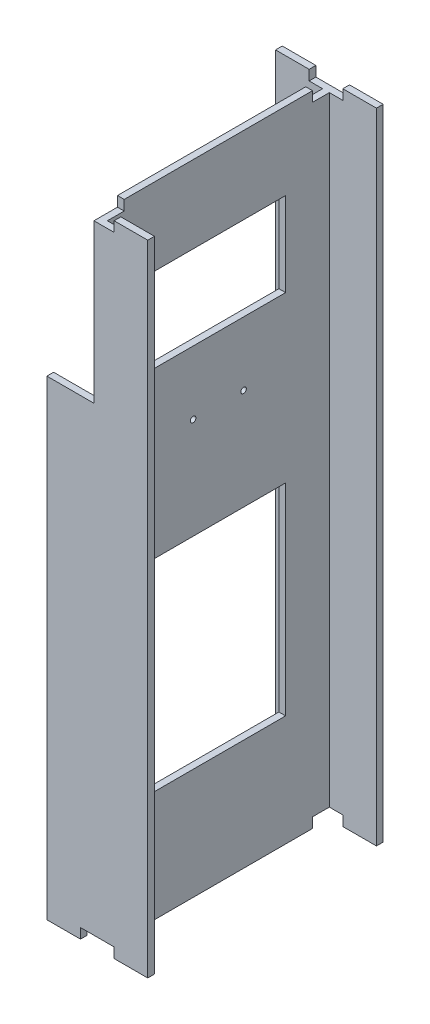
SolidWorks part; units mm, degrees
ref_plane "Front Plane" through (0, 0, 0) normal (0, 0, 1) x (1, 0, 0)
ref_plane "Top Plane" through (0, 0, 0) normal (0, 1, 0) x (1, 0, 0)
ref_plane "Right Plane" through (0, 0, 0) normal (1, 0, 0) x (0, 0, -1)
sketch "Sketch1" plane through (0, 0, 0) normal (0, 1, 0) x (1, 0, 0)
  line L0 (0, 0) -> (0, 66)
  line L2 (-16, 66) -> (-16, 68)
  line L3 (-16, 68) -> (14, 68)
  line L4 (14, 68) -> (14, 66)
  line L6 (-2, 66) -> (-2, 0)
  line L8 (14, 0) -> (14, -2)
  line L9 (14, -2) -> (-16, -2)
  line L10 (-16, -2) -> (-16, 0)
  line L12 (-16, 66) -> (-2, 66)
  line L13 (0, 66) -> (14, 66)
  line L14 (0, 0) -> (14, 0)
  line L15 (-2, 0) -> (-16, 0)
  dimension "D1" = 30
  dimension "D3" = 2
  dimension "D4" = 70
extrude "Boss-Extrude1" add sketch "Sketch1" along normal blind 95
sketch "Sketch3" plane through (0, 0, 0) normal (0, -1, 0) x (1, 0, 0)
  line L0 (48.883, 0) -> (-50.883, 0) construction
  line L1 (48.883, -66) -> (-50.883, -66) construction
  line L2 (-6, 5) -> (4, 5)
  line L3 (-6, 5) -> (-6, -5)
  line L4 (-6, -5) -> (4, -5)
  line L5 (4, 5) -> (4, -5)
  line L6 (-6, 5) -> (4, -5) construction
  line L7 (-6, -5) -> (4, 5) construction
  line L8 (-6, -61) -> (4, -61)
  line L9 (-6, -61) -> (-6, -71)
  line L10 (-6, -71) -> (4, -71)
  line L11 (4, -61) -> (4, -71)
  line L12 (-6, -61) -> (4, -71) construction
  line L13 (-6, -71) -> (4, -61) construction
  line L14 (-2, 0) -> (0, 0) construction
  line L15 (-2, -66) -> (0, -66) construction
  point P3 (-1, 0)
  point P9 (-1, -66)
  point P19 (-1, 0)
  point P24 (-1, -66)
  dimension "D1" = 10
  dimension "D2" = 10
extrude "Cut-Extrude2" cut sketch "Sketch3" against normal blind 3
mirror "Mirror2" about plane through (0, 95, 0) normal (0, -1, 0) of bodies 103
sketch "Sketch4" plane through (-2, 0, 0) normal (-1, 0, 0) x (0, 0, 1)
  line L0 (-53, 100) -> (-66, 100) construction
  line L1 (-13, 100) -> (0, 100) construction
  line L6 (-53, 167) -> (-53, 142)
  line L7 (-53, 142) -> (-13, 142)
  line L8 (-53, 167) -> (-13, 167)
  line L9 (-53, 167) -> (-53, 33) construction
  line L10 (-53, 33) -> (-13, 33)
  line L11 (-13, 167) -> (-13, 33) construction
  line L12 (-13, 142) -> (-13, 167)
  line L13 (-53, 33) -> (-53, 93)
  line L14 (-53, 93) -> (-13, 93)
  line L15 (-13, 93) -> (-13, 33)
  line L23 (-61, 0) -> (-5, 0)
  line L24 (-5, 0) -> (-5, 3)
  line L25 (-5, 3) -> (0, 3)
  line L26 (0, 3) -> (0, 187)
  line L27 (0, 187) -> (-5, 187)
  line L28 (-5, 187) -> (-5, 190)
  line L29 (-5, 190) -> (-61, 190)
  line L30 (-61, 190) -> (-61, 187)
  line L31 (-61, 187) -> (-66, 187)
  line L32 (-66, 187) -> (-66, 3)
  line L33 (-66, 3) -> (-61, 3)
  line L34 (-61, 3) -> (-61, 0)
  line L35 (-61, 0) -> (-5, 0) construction
  line L36 (-5, 0) -> (-5, 3) construction
  line L37 (-5, 3) -> (0, 3) construction
  line L38 (0, 3) -> (0, 187) construction
  line L39 (0, 187) -> (-5, 187) construction
  line L40 (-5, 187) -> (-5, 190) construction
  line L41 (-5, 190) -> (-61, 190) construction
  line L42 (-61, 190) -> (-61, 187) construction
  line L43 (-61, 187) -> (-66, 187) construction
  line L44 (-66, 187) -> (-66, 3) construction
  line L45 (-66, 3) -> (-61, 3) construction
  line L46 (-61, 3) -> (-61, 0) construction
  dimension "D1" = 30
  dimension "D3" = 40
  dimension "D2" = 20
  dimension "D5" = 60
  dimension "D6" = 25
  dimension "D4" = 0
extrude "Cut-Extrude8" cut sketch "Sketch4" against normal blind 2
sketch "Sketch5" plane through (0, 0, 0) normal (0, 0, -1) x (-1, 0, 0)
  line L1 (2, 190) -> (16, 190)
  line L2 (2, 190) -> (2, 140)
  line L3 (2, 140) -> (16, 140)
  line L4 (16, 190) -> (16, 140)
  line L5 (2, 187) -> (2, 3) construction
  point P5 (9.518, 195.2569)
  point P6 (-6.1067, 194.6282)
  point P7 (0, 169.7844)
  point P8 (0, 0)
  point P10 (3.0538, 160)
  dimension "D1" = 50
extrude "Cut-Extrude9" cut sketch "Sketch5" against normal up to surface (2 mm away) up to face at (-1, 95, 2)
sketch "Sketch6" plane through (0, 0, 0) normal (1, 0, 0) x (0, 0, -1)
  circle A0 centre (40.5, 123.0748) radius 0.825 construction
  circle A1 centre (25.5, 123.0748) radius 0.825 construction
  circle A2 centre (40.5, 123.0748) radius 0.825
  circle A3 centre (25.5, 123.0748) radius 0.825
extrude "Cut-Extrude10" cut sketch "Sketch6" against normal through all
equation "\"w_BeamWidth\"=30"
equation "\"D1@Sketch1\"=\"w_BeamWidth\""
equation "\"TBeam\"=2"
equation "\"D2@Sketch1\"=\"TBeam\""
equation "\"D3@Sketch1\"=\"TBeam\""
equation "\"BeamLength\"= 70"
equation "\"D4@Sketch1\"=\"BeamLength\""
equation "\"BeamHeight\"= 190"
equation "\"D1@Boss-Extrude1\"=\"BeamHeight\"/2"
equation "\"HoleHeightInBeam\"=160"
equation "\"HoleSizeInBeam\"=40"
equation "\"D3@Sketch4\"=\"HoleSizeInBeam\""
equation "\"D1@Cut-Extrude8\" = \"TBeam\""
equation "\"HoleHieght1\"=60"
equation "\"D5@Sketch4\"=\"HoleHieght1\""
equation "\"HoleHieght2\"=25"
equation "\"D6@Sketch4\"=\"HoleHieght2\""
equation "\"CounterWeightCutoutHeight\"=50"
equation "\"D1@Sketch5\"=\"CounterWeightCutoutHeight\""
